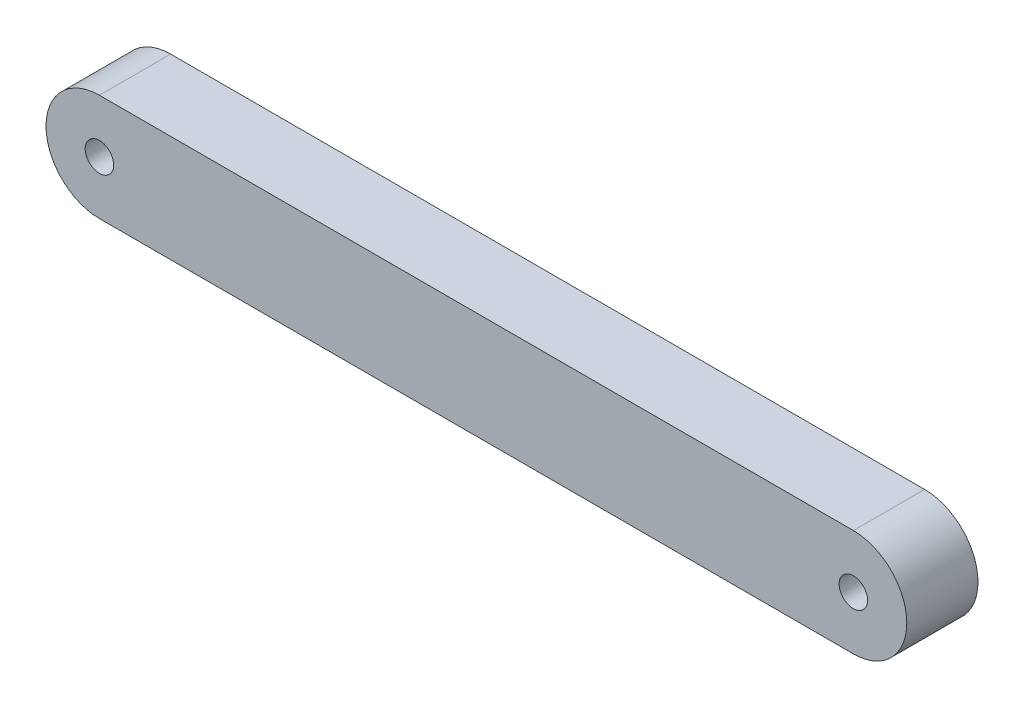
SolidWorks part; units mm, degrees
ref_plane "前视基准面" through (0, 0, 0) normal (0, 0, 1) x (1, 0, 0)
ref_plane "上视基准面" through (0, 0, 0) normal (0, 1, 0) x (1, 0, 0)
ref_plane "右视基准面" through (0, 0, 0) normal (1, 0, 0) x (0, 0, -1)
other "Configuration Table"
sketch "草图1" plane through (0, 0, 0) normal (0, 0, 1) x (1, 0, 0)
  line L0 (0, 0) -> (211.7, 0) construction
  line L1 (0, 15) -> (211.7, 15)
  line L2 (0, -15) -> (211.7, -15)
  arc A0 (0, 15) -> (0, -15) centre (0, 0) ccw
  circle A1 centre (0, 0) radius 4
  arc A2 (211.7, -15) -> (211.7, 15) centre (211.7, 0) ccw
  circle A3 centre (211.7, 0) radius 4
extrude "凸台-拉伸1" add sketch "草图1" along normal blind 20
